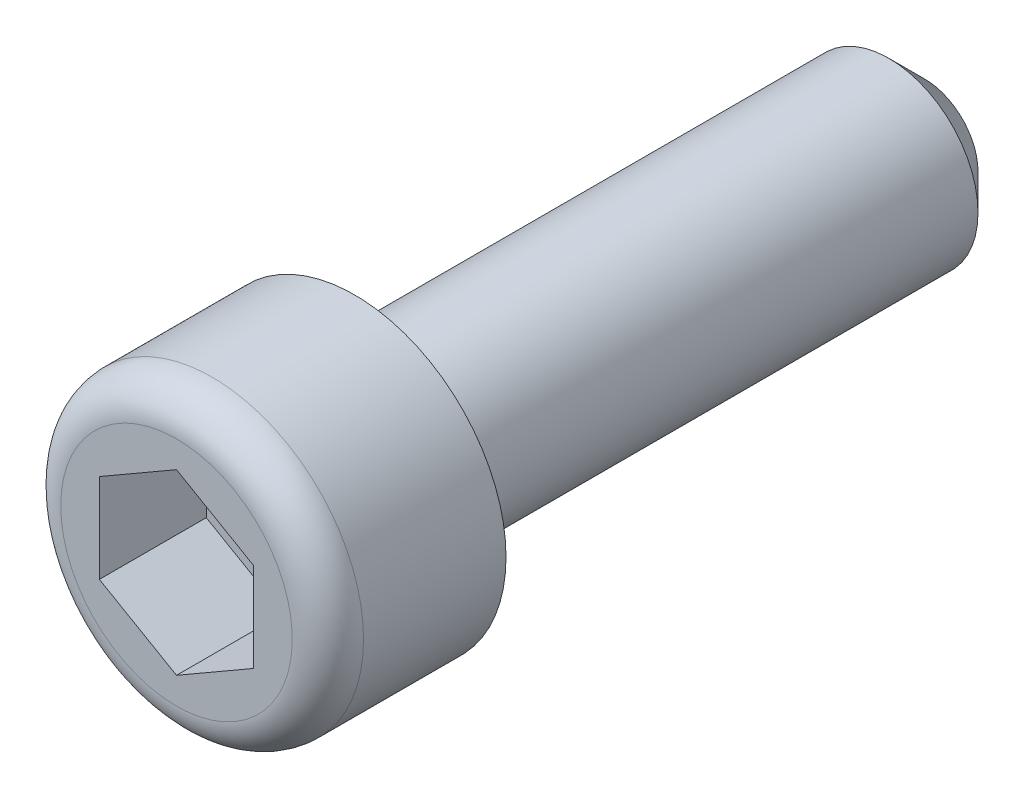
SolidWorks part; units mm, degrees
ref_plane "Front Plane" through (0, 0, 0) normal (0, 0, 1) x (1, 0, 0)
ref_plane "Top Plane" through (0, 0, 0) normal (0, 1, 0) x (1, 0, 0)
ref_plane "Right Plane" through (0, 0, 0) normal (1, 0, 0) x (0, 0, -1)
sketch "Sketch1" plane through (0, 0, 0) normal (1, 0, 0) x (0, 0, -1)
  line L0 (-156.2916, 0) -> (7658.2872, 0) construction
  line L1 (0, 0) -> (0, 4.25)
  line L2 (0, 4.25) -> (5, 4.25)
  line L3 (5, 4.25) -> (5, 2.5)
  line L4 (5, 2.5) -> (21, 2.5)
  line L5 (21, 2.5) -> (21, 0)
  line L6 (21, 0) -> (0, 0)
  dimension "D1" = 5
  dimension "D2" = 16
  dimension "D3" = 5
  dimension "D4" = 8.5
revolve "Body" add sketch "Sketch1" angle 360 about L0
sketch "Sketch2" plane through (0, 0, 0) normal (0, 0, 1) x (1, 0, 0)
  line L1 (0, 2.5) -> (-2.1651, 1.25)
  line L2 (-2.1651, 1.25) -> (-2.1651, -1.25)
  line L3 (-2.1651, -1.25) -> (0, -2.5)
  line L4 (0, -2.5) -> (2.1651, -1.25)
  line L5 (2.1651, -1.25) -> (2.1651, 1.25)
  line L6 (2.1651, 1.25) -> (0, 2.5)
  circle A0 centre (0, 0) radius 2.5 construction
  dimension "D1" = 5
extrude "Footprint" cut sketch "Sketch2" against normal blind 3
chamfer "Chamfer1" distance 1 angle 45 1 edges at (2.5, 0, -21)
fillet "Fillet1" radius 1 1 edges at (4.25, 0, 0)
